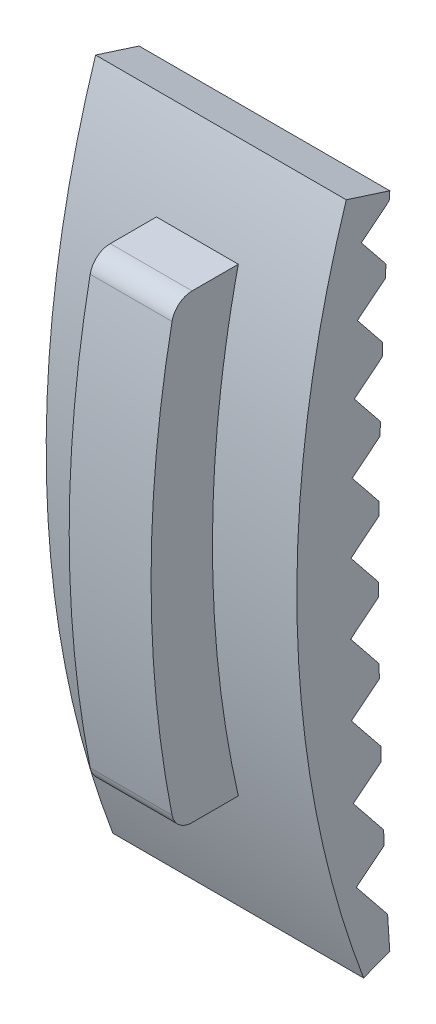
SolidWorks part; units mm, degrees
ref_plane "Front Plane" through (0, 0, 0) normal (0, 0, 1) x (1, 0, 0)
ref_plane "Top Plane" through (0, 0, 0) normal (0, 1, 0) x (1, 0, 0)
ref_plane "Right Plane" through (0, 0, 0) normal (1, 0, 0) x (0, 0, -1)
sketch "Sketch1" plane through (0, 0, 0) normal (0, 0, 1) x (1, 0, 0)
  line L0 (0, 0) -> (0, -27.8746) construction
  line L1 (-15.5575, 57.15) -> (15.5575, 57.15)
  line L2 (-15.5575, 57.15) -> (-15.5575, -57.15)
  line L3 (-15.5575, -57.15) -> (-7.8455, -57.15)
  line L4 (15.5575, 57.15) -> (15.5575, -57.15)
  line L5 (-15.5575, 57.15) -> (15.5575, -57.15) construction
  line L6 (-15.5575, -57.15) -> (15.5575, 57.15) construction
  line L7 (7.8455, -57.15) -> (9.525, -66.675)
  line L8 (-7.8455, -57.15) -> (-9.525, -66.675)
  line L9 (-9.525, -66.675) -> (9.525, -66.675)
  line L10 (7.8455, -57.15) -> (15.5575, -57.15)
  point P0 (0, 0)
  point P12 (0, -66.675)
  dimension "D1" = 31.115
  dimension "D2" = 114.3
  dimension "D3" = 20
  dimension "D4" = 19.05
  dimension "D5" = 9.525
extrude "Boss-Extrude1" add sketch "Sketch1" along normal blind 63.5
sketch "Sketch2" plane through (15.5575, 0, 0) normal (1, 0, 0) x (0, 0, -1)
  line L0 (-63.5, -57.15) -> (0, -57.15) construction
  line L1 (0, -66.675) -> (-6.985, -66.675)
  line L2 (0, -66.675) -> (0, -57.15)
  line L3 (0, -57.15) -> (-6.985, -57.15)
  line L4 (-6.985, -66.675) -> (-6.985, -57.15)
  dimension "D1" = 6.985
extrude "Cut-Extrude1" cut sketch "Sketch2" against normal through all
sketch "Sketch3" plane through (15.5575, 0, 0) normal (1, 0, 0) x (0, 0, -1)
  line L14 (-63.5, 57.15) -> (0, 57.15) construction
  line L15 (-63.5, -57.15) -> (-63.5, 57.15) construction
  line L16 (-63.5, -66.675) -> (-63.5, -57.15) construction
  line L17 (0, -57.15) -> (0, 57.15) construction
  line L18 (-63.5, -66.675) -> (-63.5, -57.15)
  line L19 (-63.5, -57.15) -> (-63.5, 57.15)
  line L20 (-63.5, 57.15) -> (-6.5418, 57.15)
  line L21 (0, -57.15) -> (0, 49.1802)
  arc A4 (-6.5418, 57.15) -> (-63.5, -66.675) centre (99.5746, -66.675) ccw
  arc A5 (0, 49.1802) -> (0, -57.15) centre (117.4009, -3.9849) ccw
extrude "Cut-Extrude2" cut sketch "Sketch3" against normal through all
sketch "Sketch6" plane through (15.5575, 0, 0) normal (1, 0, 0) x (0, 0, -1)
  line L9 (-54.9317, -49.53) -> (-11.2743, -49.53)
  arc A4 (-47.6321, -49.8905) -> (-54.2674, -44.3419) centre (-49.2401, -45.0717) cw
  arc A5 (-19.6843, -49.3294) -> (-13.4029, -42.9981) centre (-18.271, -44.45) ccw
  arc A6 (-10.8486, 42.7455) -> (-11.2743, -49.53) centre (117.4009, -3.9849) ccw
  arc A7 (-10.8486, 42.7455) -> (-54.9317, -49.53) centre (99.5746, -66.675) ccw
  arc A8 (-10.8486, 42.7455) -> (-13.4029, -42.9981) centre (117.4009, -3.9849) ccw
  arc A9 (-10.8486, 42.7455) -> (-54.2674, -44.3419) centre (99.5746, -66.675) ccw
  arc A10 (-47.6321, -49.8905) -> (-19.6843, -49.3294) centre (-32.7578, -94.4642) cw
  dimension "D2" = 5.08
  dimension "1.85" = 46.99
  dimension "D1" = 7.62
extrude "Cut-Extrude3" cut sketch "Sketch6" against normal through all
fillet "Fillet1" radius 2.54 1 edges at (0, 42.7455, 10.8486)
sketch "Sketch7" plane through (0, 0, 0) normal (1, 0, 0) x (0, 0, -1)
  line L0 (-19.0969, 24.5901) -> (-8.2692, 24.5901)
  line L1 (-8.2692, -32.5599) -> (-19.0969, -32.5599)
  line L2 (-19.0969, 24.5901) -> (-19.0969, -32.5599)
  arc A0 (0, 49.1802) -> (0, -57.15) centre (117.4009, -3.9849) ccw construction
  arc A1 (-14.2891, 31.9235) -> (-13.4029, -42.9981) centre (117.4009, -3.9849) ccw construction
  arc A2 (-8.2692, 24.5901) -> (-8.2692, -32.5599) centre (117.4009, -3.9849) ccw
  point P10 (-19.0969, -3.9849)
  point P11 (-11.4769, -3.9849)
  dimension "D1" = 57.15
extrude "Cut-Extrude4" cut sketch "Sketch7" against normal mid plane 10.16
sketch "Sketch9" plane through (15.5575, 0, 0) normal (1, 0, 0) x (0, 0, -1)
  line L0 (-6.5418, 57.15) -> (0, 49.1802)
ref_plane "Plane2" through (15.5575, 57.15, 6.5418) normal (0, -0.773, -0.6345) x (-1, 0, 0)
sketch "Sketch10" plane through (15.5575, 57.15, 6.5418) normal (0, -0.773, -0.6345) x (-1, 0, 0)
  line L4 (15.5575, 5.0565) -> (15.5575, 19.0294) construction
  line L5 (0, 5.0565) -> (31.115, 5.0565) construction
  line L6 (0, 5.0565) -> (6.985, 5.0565)
  line L7 (6.985, 5.0565) -> (0, -3.77)
  line L8 (0, 0) -> (0, -67.4621) construction
  line L9 (0, 5.0565) -> (0, -3.77)
  line L10 (31.115, 5.0565) -> (31.115, -3.77)
  line L11 (24.13, 5.0565) -> (31.115, -3.77)
  line L12 (31.115, 5.0565) -> (24.13, 5.0565)
  dimension "D1" = 8.8265
  dimension "D2" = 6.985
extrude "Cut-Extrude6" cut sketch "Sketch10" against normal mid plane 30.226
fillet "Fillet2" radius 0.508 5 edges at (-15.5575, 4.0784, 47.3515) (-14.0661, 55.9145, 7.9668) (0, 57.15, 6.5418) (15.5575, 4.0784, 47.3515) (14.0661, 55.9145, 7.9668)
sketch "Sketch11" plane through (15.5575, 0, 0) normal (1, 0, 0) x (0, 0, -1)
  line L0 (-5.3458, 35.2928) -> (0.0551, 33.5646)
  line L1 (-3.1992, -49.4284) -> (0.0551, -48.2022)
  arc A0 (-1.6848, 45.2907) -> (0, -57.15) centre (117.4009, -3.9849) ccw construction
  arc A1 (-5.3458, 35.2928) -> (-3.1992, -49.4284) centre (117.4009, -3.9849) ccw
  arc A3 (0.0551, 33.5646) -> (0.0551, -48.2022) centre (597.5156, -7.3188) ccw
extrude "Boss-Extrude2" add sketch "Sketch11" against normal up to surface (31.115 mm away) separate body up to face at (-15.5575, -19.629, 29.589)
sketch "Sketch12" plane through (0, 0, 0) normal (1, 0, 0) x (0, 0, -1)
  line L0 (-16.0724, 24.5901) -> (-8.2692, 24.5901)
  line L1 (-8.2692, -32.5599) -> (-16.0724, -32.5599)
  arc A0 (-1.6848, 45.2907) -> (0, -57.15) centre (117.4009, -3.9849) ccw construction
  arc A1 (-14.2891, 31.9235) -> (-13.4029, -42.9981) centre (117.4009, -3.9849) ccw construction
  arc A2 (-8.2692, 24.5901) -> (-8.2692, -32.5599) centre (117.4009, -3.9849) ccw
  arc A3 (-16.0724, 24.5901) -> (-16.0724, -32.5599) centre (117.4009, -3.9849) ccw
extrude "Boss-Extrude3" add sketch "Sketch12" along normal mid plane 10.16 separate body
delete or keep bodies "Body-Delete/Keep 1" type delete bodies bodies 107
sketch "Sketch13" plane through (15.5575, 0, 0) normal (1, 0, 0) x (0, 0, -1)
  line L4 (-0.0155, 32.5204) -> (3.0463, 28.7104)
  line L10 (-0.0155, 32.5204) -> (-3.4803, 29.736)
  line L11 (3.0463, 28.7104) -> (-0.4186, 25.926)
  line L12 (-3.4803, 29.736) -> (-0.4186, 25.926)
  line L13 (0.0551, 33.5646) -> (-5.3458, 35.2928) construction
  line L17 (-0.5011, 24.4068) -> (2.6459, 20.4906)
  line L18 (-0.5011, 24.4068) -> (-3.966, 21.6224)
  line L19 (2.6459, 20.4906) -> (-0.819, 17.7063)
  line L20 (-3.966, 21.6224) -> (-0.819, 17.7063)
  line L21 (-0.8816, 16.1622) -> (2.3548, 12.1348)
  line L22 (-0.8816, 16.1622) -> (-4.3464, 13.3778)
  line L23 (2.3548, 12.1348) -> (-1.11, 9.3505)
  line L24 (-4.3464, 13.3778) -> (-1.11, 9.3505)
  line L25 (-1.1517, 7.7803) -> (2.1785, 3.6362)
  line L26 (-1.1517, 7.7803) -> (-4.6166, 4.996)
  line L27 (2.1785, 3.6362) -> (-1.2863, 0.8518)
  line L28 (-4.6166, 4.996) -> (-1.2863, 0.8518)
  line L29 (-1.306, -0.7456) -> (2.123, -5.0126)
  line L30 (-1.306, -0.7456) -> (-4.7709, -3.53)
  line L31 (2.123, -5.0126) -> (-1.3419, -7.797)
  line L32 (-4.7709, -3.53) -> (-1.3419, -7.797)
  line L33 (-1.3384, -9.4233) -> (2.1948, -13.82)
  line L34 (-1.3384, -9.4233) -> (-4.8033, -12.2077)
  line L35 (2.1948, -13.82) -> (-1.2701, -16.6044)
  line L36 (-4.8033, -12.2077) -> (-1.2701, -16.6044)
  line L37 (-4.707, -21.0455) -> (-1.0636, -25.5793)
  line L38 (-4.707, -21.0455) -> (-1.2421, -18.2611)
  line L39 (-1.0636, -25.5793) -> (2.4012, -22.7949)
  line L40 (-1.2421, -18.2611) -> (2.4012, -22.7949)
  line L41 (-1.0097, -27.2683) -> (2.7505, -31.9476)
  line L42 (-1.0097, -27.2683) -> (-4.4746, -30.0527)
  line L43 (2.7505, -31.9476) -> (-0.7143, -34.7319)
  line L44 (-4.4746, -30.0527) -> (-0.7143, -34.7319)
  line L45 (-0.6329, -36.4553) -> (3.2518, -41.2893)
  line L46 (-0.6329, -36.4553) -> (-4.0977, -39.2396)
  line L47 (3.2518, -41.2893) -> (-0.2131, -44.0737)
  line L48 (-4.0977, -39.2396) -> (-0.2131, -44.0737)
  arc A1 (0.0551, 33.5646) -> (0.0551, -48.2022) centre (597.5156, -7.3188) ccw construction
  dimension "D1" = 1.016
  dimension "D2" = 3.81
  dimension "D3" = 4.445
  dimension "D4" = 1.016
  dimension "D5" = 1.016
  dimension "D6" = 1.016
  dimension "D7" = 1.016
  dimension "D8" = 1.016
  dimension "D9" = 1.016
  dimension "D10" = 1.016
  dimension "D11" = 1.016
extrude "Cut-Extrude7" cut sketch "Sketch13" against normal through all
fillet "Fillet3" radius 2.54 2 edges at (0, -32.5599, 16.0724) (0, 24.5901, 16.0724)
